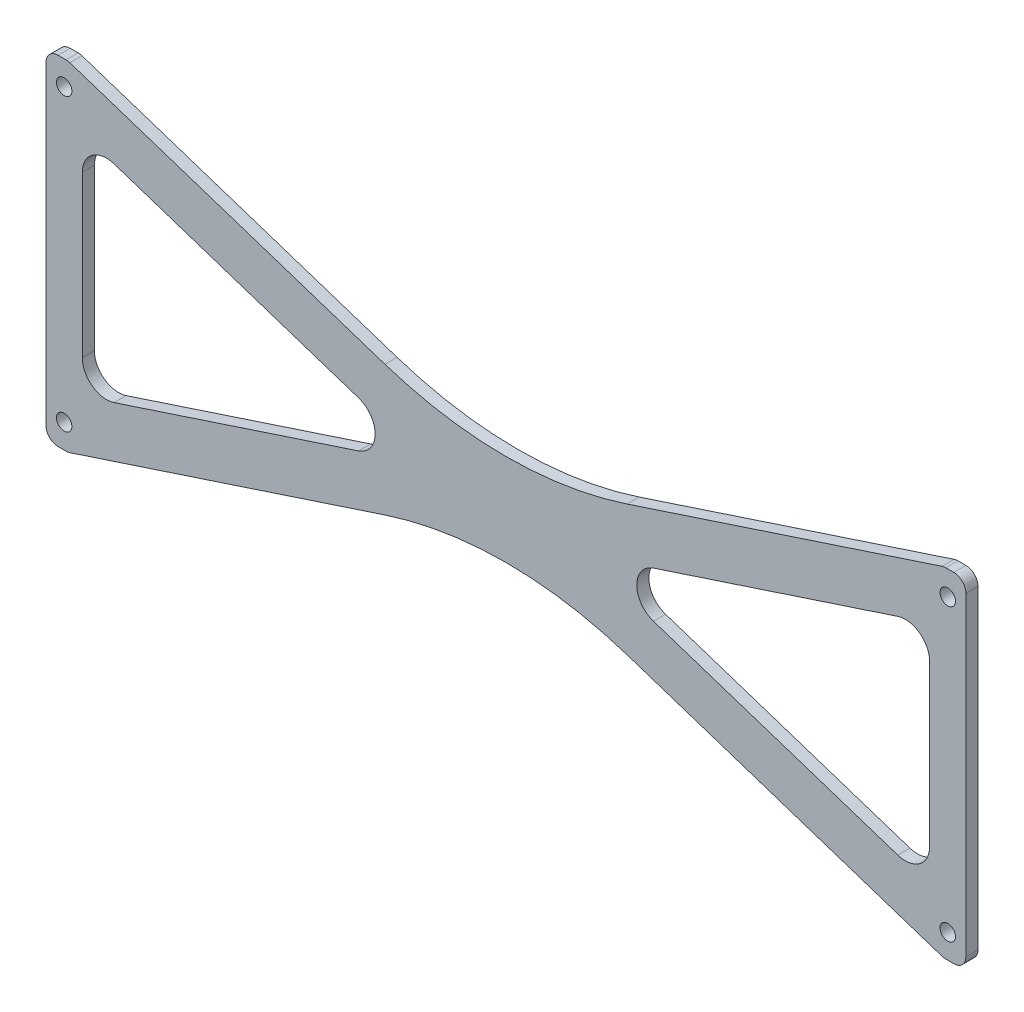
SolidWorks part; units mm, degrees
ref_plane "Front Plane" through (0, 0, 0) normal (0, 0, 1) x (1, 0, 0)
ref_plane "Top Plane" through (0, 0, 0) normal (0, 1, 0) x (1, 0, 0)
ref_plane "Right Plane" through (0, 0, 0) normal (1, 0, 0) x (0, 0, -1)
sketch "Sketch1" plane through (0, 0, 0) normal (0, 0, 1) x (1, 0, 0)
  line L1 (-120.65, -44.45) -> (120.65, -44.45)
  line L2 (-120.65, -44.45) -> (-120.65, 44.45)
  line L3 (-120.65, 44.45) -> (120.65, 44.45)
  line L4 (120.65, -44.45) -> (120.65, 44.45)
  line L5 (-120.65, -44.45) -> (120.65, 44.45) construction
  line L6 (-120.65, 44.45) -> (120.65, -44.45) construction
  line L7 (-115.8875, -38.1) -> (115.8875, -38.1)
  line L8 (-115.8875, -38.1) -> (-115.8875, 38.1)
  line L9 (-115.8875, 38.1) -> (115.8875, 38.1)
  line L10 (115.8875, -38.1) -> (115.8875, 38.1)
  line L11 (-115.8875, -38.1) -> (115.8875, 38.1) construction
  line L12 (-115.8875, 38.1) -> (115.8875, -38.1) construction
  point P0 (0, 0)
  point P5 (0, 0)
  dimension "D1" = 241.3
  dimension "D2" = 88.9
  dimension "D3" = 76.2
  dimension "D4" = 4.7625
sketch "Sketch2" plane through (0, 0, 0) normal (0, 0, 1) x (1, 0, 0)
  line L0 (120.65, -44.45) -> (120.65, 44.45) construction
  line L1 (-120.65, -44.45) -> (-120.65, 44.45) construction
  line L2 (120.65, -44.45) -> (120.65, 44.45)
  line L3 (-120.65, -44.45) -> (-120.65, 44.45)
  line L9 (-117.8707, 32.0676) -> (113.9043, -44.1324)
  line L10 (-111.125, 29.8499) -> (-20.3316, 0)
  line L11 (-113.9043, 44.1324) -> (117.8707, -32.0676)
  line L12 (-114.8704, 44.45) -> (0, 6.6844)
  line L13 (0, 6.6844) -> (114.8704, 44.45)
  line L14 (-113.9043, -44.1324) -> (117.8707, 32.0676)
  line L15 (-114.8704, -44.45) -> (0, -6.6844)
  line L16 (-117.8707, -32.0676) -> (113.9043, 44.1324)
  line L17 (-111.125, -29.8499) -> (-20.3316, 0)
  line L18 (0, -6.6844) -> (114.8704, -44.45)
  line L19 (20.3316, 0) -> (111.125, -29.8499)
  line L20 (20.3316, 0) -> (111.125, 29.8499)
  line L21 (-120.65, 44.45) -> (120.65, 44.45) construction
  line L22 (-120.65, -44.45) -> (120.65, -44.45) construction
  line L23 (-120.65, -44.45) -> (-114.8704, -44.45)
  line L24 (-120.65, 44.45) -> (-114.8704, 44.45)
  line L25 (114.8704, 44.45) -> (120.65, 44.45)
  line L26 (114.8704, -44.45) -> (120.65, -44.45)
  line L27 (-111.125, 29.8499) -> (-111.125, -29.8499)
  line L28 (111.125, 29.8499) -> (111.125, -29.8499)
  dimension "D5" = 9.525
  dimension "D1" = 6.35
  dimension "D2" = 6.35
  dimension "D3" = 6.35
  dimension "D4" = 6.35
extrude "Boss-Extrude1" add sketch "Sketch2" along normal blind 3.175
sketch "Sketch3" plane through (0, 0, 3.175) normal (0, 0, 1) x (1, 0, 0)
  circle A0 centre (-115.8875, 38.1) radius 2.032
  circle A1 centre (-115.8875, -38.1) radius 2.032
  circle A2 centre (115.8875, 38.1) radius 2.032
  circle A3 centre (115.8875, -38.1) radius 2.032
  dimension "D1" = 4.064
extrude "Cut-Extrude1" cut sketch "Sketch3" against normal through all
fillet "Fillet1" radius 3.175 8 edges at (120.65, -44.45, 1.5875) (120.65, 44.45, 1.5875) (-120.65, -44.45, 1.5875) (-120.65, 44.45, 1.5875) (114.8704, 44.45, 1.5875) (-114.8704, 44.45, 1.5875) (-114.8704, -44.45, 1.5875) (114.8704, -44.45, 1.5875)
fillet "Fillet2" radius 101.6 2 edges at (0, -6.6844, 1.5875) (0, 6.6844, 1.5875)
fillet "Fillet3" radius 6.35 6 edges at (-111.125, -29.8499, 1.5875) (-111.125, 29.8499, 1.5875) (111.125, 29.8499, 1.5875) (111.125, -29.8499, 1.5875) (-20.3316, 0, 1.5875) (20.3316, 0, 1.5875)
